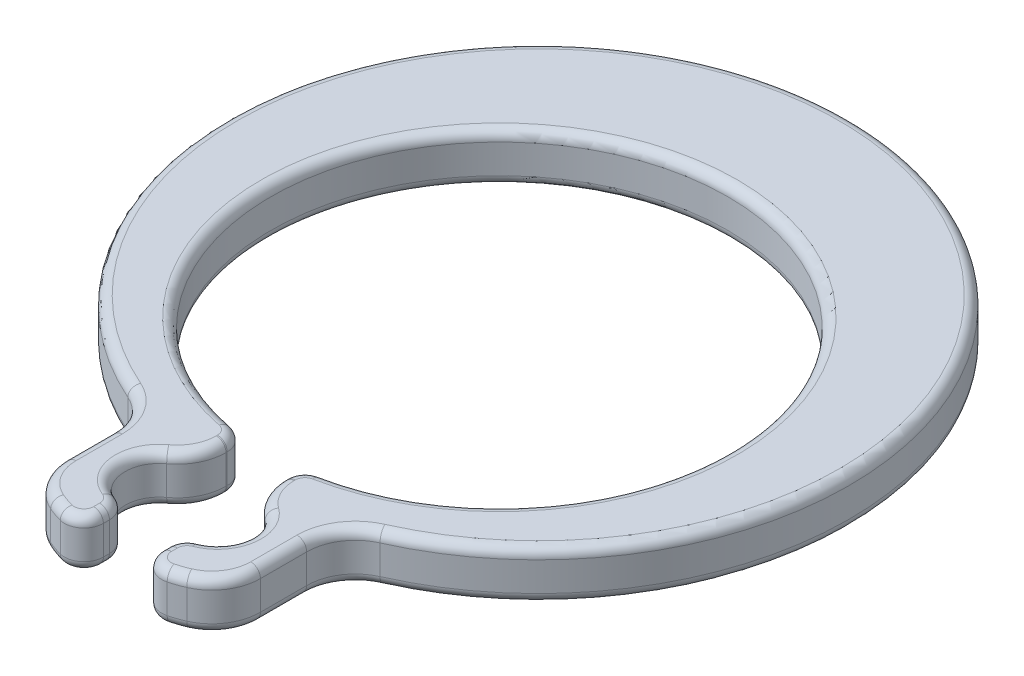
SolidWorks part; units mm, degrees
ref_plane "前视基准面" through (0, 0, 0) normal (0, 0, 1) x (1, 0, 0)
ref_plane "上视基准面" through (0, 0, 0) normal (0, 1, 0) x (1, 0, 0)
ref_plane "右视基准面" through (0, 0, 0) normal (1, 0, 0) x (0, 0, -1)
other "Configuration Table"
sketch "草图1" plane through (0, 0, 0) normal (0, 1, 0) x (1, 0, 0)
  line L0 (-1.4772, 0) -> (2.5, 0) construction
  line L1 (0, 1.545) -> (0, -4.157) construction
  line L6 (0.3, -2.3308) -> (0.3, -2.85)
  line L7 (1, -2.6397) -> (1, -3.7141)
  line L8 (0.3, -3.55) -> (0.3, -4)
  line L9 (-0.3, -3.55) -> (-0.3, -4)
  line L10 (-1, -2.6397) -> (-1, -3.7141)
  line L11 (-0.3, -2.3308) -> (-0.3, -2.85)
  arc A0 (0.3, -2.3308) -> (-0.3, -2.3308) centre (0, 0) ccw
  arc A1 (1, -2.6397) -> (-1, -2.6397) centre (0, 0.4) ccw
  arc A6 (0.3, -4) -> (1, -3.7141) centre (0.3, -3) ccw
  arc A7 (0.3, -3.55) -> (0.3, -2.85) centre (0.3, -3.2) ccw
  arc A8 (-0.3, -3.55) -> (-0.3, -2.85) centre (-0.3, -3.2) cw
  arc A9 (-0.3, -4) -> (-1, -3.7141) centre (-0.3, -3) cw
  point P16 (-0.3253, -2.3308)
  point P17 (0.3, -3.9908)
  point P26 (-1.0243, -2.6397)
  dimension "D1" = 4.7
  dimension "D2" = 6.4
  dimension "D6" = 3.2
  dimension "D7" = 1
  dimension "D5" = 0.7
  dimension "D3" = 0.4
  dimension "D4" = 0.3
  dimension "D8" = 3
  dimension "D9" = 1
extrude "凸台-拉伸1" add sketch "草图1" along normal blind 0.5
fillet "圆角3" radius 0.5 6 edges at (-0.3, 0.25, 2.85) (0.3, 0.25, 2.85) (1, 0.25, 3.7141) (-1, 0.25, 3.7141) (-1, 0.25, 2.6397) (1, 0.25, 2.6397)
fillet "圆角4" radius 0.2 6 edges at (-0.3, 0.25, 2.3308) (0.3, 0.25, 2.3308) (0.3, 0.25, 3.55) (-0.3, 0.25, 3.55) (-0.3, 0.25, 4) (0.3, 0.25, 4)
fillet "圆角5" radius 0.1 48 edges at (0.3453, 0, 2.3737) (0.3, 0, 2.5066) (0.3544, 0, 2.7395) (0.6471, 0, 3.2448) (0.3349, 0, 3.5995) (0.3, 0, 3.7435) (0.3775, 0, 3.9327) (0.626, 0, 3.9454) (0.9183, 0, 3.7321) (1, 0, 3.2203) (1.0809, 0, 2.7097) (0, 0, -3.6) (-1.0809, 0, 2.7097) (-1, 0, 3.2203) (-0.9183, 0, 3.7321) (-0.626, 0, 3.9454) (-0.3775, 0, 3.9327) (-0.3, 0, 3.7435) (-0.3349, 0, 3.5995) (-0.6471, 0, 3.2448) (-0.3544, 0, 2.7395) (-0.3, 0, 2.5066) (-0.3453, 0, 2.3737) (0, 0, -2.35) (-0.3544, 0.5, 2.7395) (-0.6471, 0.5, 3.2448) (-0.3349, 0.5, 3.5995) (-0.3, 0.5, 3.7435) (-0.3775, 0.5, 3.9327) (-0.626, 0.5, 3.9454) (-0.9183, 0.5, 3.7321) (-1, 0.5, 3.2203) (-1.0809, 0.5, 2.7097) (0, 0.5, -3.6) (1.0809, 0.5, 2.7097) (1, 0.5, 3.2203) (0.9183, 0.5, 3.7321) (0.626, 0.5, 3.9454) (0.3775, 0.5, 3.9327) (0.3, 0.5, 3.7435) (0.3349, 0.5, 3.5995) (0.6471, 0.5, 3.2448) (0.3544, 0.5, 2.7395) (0.3, 0.5, 2.5066) (0.3453, 0.5, 2.3737) (0, 0.5, -2.35) (-0.3453, 0.5, 2.3737) (-0.3, 0.5, 2.5066)
